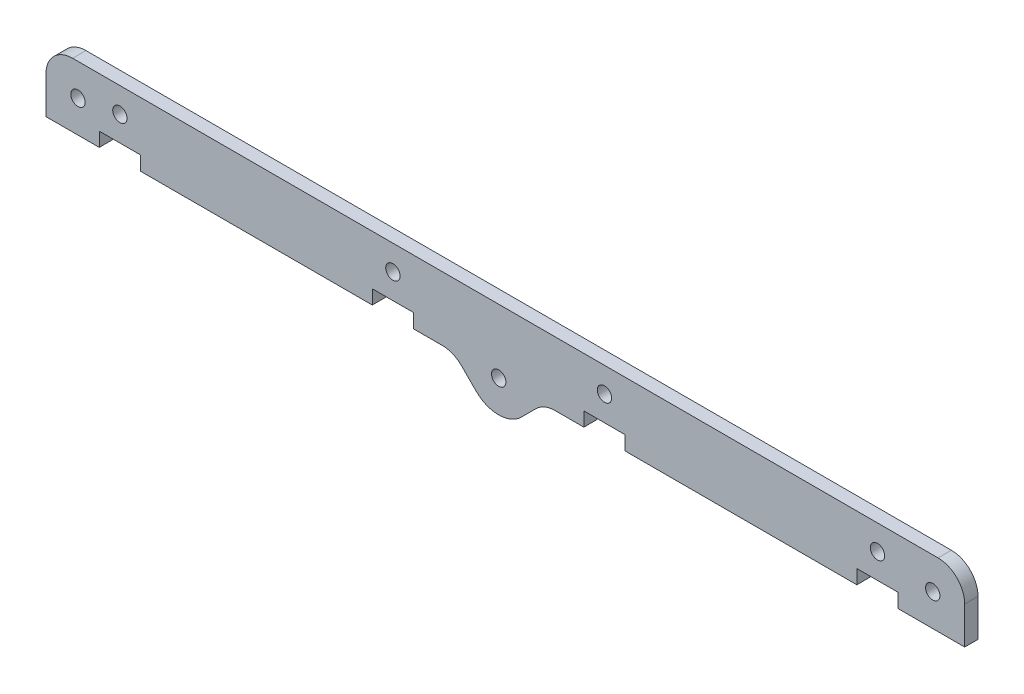
SolidWorks part; units mm, degrees
ref_plane "Front Plane" through (0, 0, 0) normal (0, 0, 1) x (1, 0, 0)
ref_plane "Top Plane" through (0, 0, 0) normal (0, 1, 0) x (1, 0, 0)
ref_plane "Right Plane" through (0, 0, 0) normal (1, 0, 0) x (0, 0, -1)
sketch "Sketch1" plane through (0, 0, 0) normal (0, 0, 1) x (1, 0, 0)
  line L0 (0, 12) -> (345, 12) construction
  line L1 (0, 0) -> (20, 0)
  line L2 (0, 0) -> (0, 24)
  line L3 (0, 24) -> (345, 24)
  line L4 (345, 0) -> (345, 24)
  line L5 (161.5147, -8.4853) -> (153.0294, 0)
  line L6 (178.4853, -8.4853) -> (186.9706, 0)
  line L7 (186.9706, 0) -> (201.9706, 0)
  line L8 (138.0294, 0) -> (153.0294, 0)
  line L10 (138.0294, 0) -> (138.0294, 5.3)
  line L11 (138.0294, 5.3) -> (122.5294, 5.3)
  line L12 (122.5294, 0) -> (122.5294, 5.3)
  line L14 (201.9706, 0) -> (201.9706, 5.3)
  line L15 (201.9706, 5.3) -> (217.4706, 5.3)
  line L16 (217.4706, 0) -> (217.4706, 5.3)
  line L18 (35.5, 0) -> (35.5, 5.3)
  line L19 (35.5, 5.3) -> (20, 5.3)
  line L20 (20, 0) -> (20, 5.3)
  line L22 (304.5, 0) -> (304.5, 5.3)
  line L23 (304.5, 5.3) -> (320, 5.3)
  line L24 (320, 0) -> (320, 5.3)
  line L25 (217.4706, 0) -> (304.5, 0)
  line L26 (320, 0) -> (345, 0)
  line L27 (35.5, 0) -> (122.5294, 0)
  line L28 (27.75, 5.3) -> (27.75, 24) construction
  circle A1 centre (170, 0) radius 2.7
  circle A2 centre (12, 12) radius 2.7
  circle A3 centre (333, 12) radius 2.7
  arc A4 (161.5147, -8.4853) -> (178.4853, -8.4853) centre (170, 0) ccw
  circle A5 centre (27.75, 14.65) radius 2.7
  circle A6 centre (130.2794, 14.65) radius 2.7
  circle A7 centre (209.7206, 14.65) radius 2.7
  circle A8 centre (312.25, 14.65) radius 2.7
  point P43 (0, 0)
  point P44 (0, 0)
  point P45 (130.2794, 5.3)
  point P46 (0, 0)
  point P47 (209.7206, 5.3)
  point P48 (0, 0)
  point P49 (312.25, 5.3)
  dimension "D3" = 5.4
  dimension "D4" = 45
  dimension "D6" = 12
  dimension "D1" = 24
  dimension "D2" = 345
  dimension "D5" = 45
  dimension "D7" = 12
  dimension "D8" = 12
  dimension "D9" = 15.5
  dimension "D10" = 5.3
  dimension "D11" = 20
  dimension "D12" = 25
  dimension "D13" = 15
  dimension "D14" = 15
  dimension "D15" = 9.35
extrude "Boss-Extrude1" add sketch "Sketch1" along normal blind 5
fillet "Fillet1" radius 10 4 edges at (186.9706, 0, 2.5) (345, 24, 2.5) (0, 24, 2.5) (153.0294, 0, 2.5)
